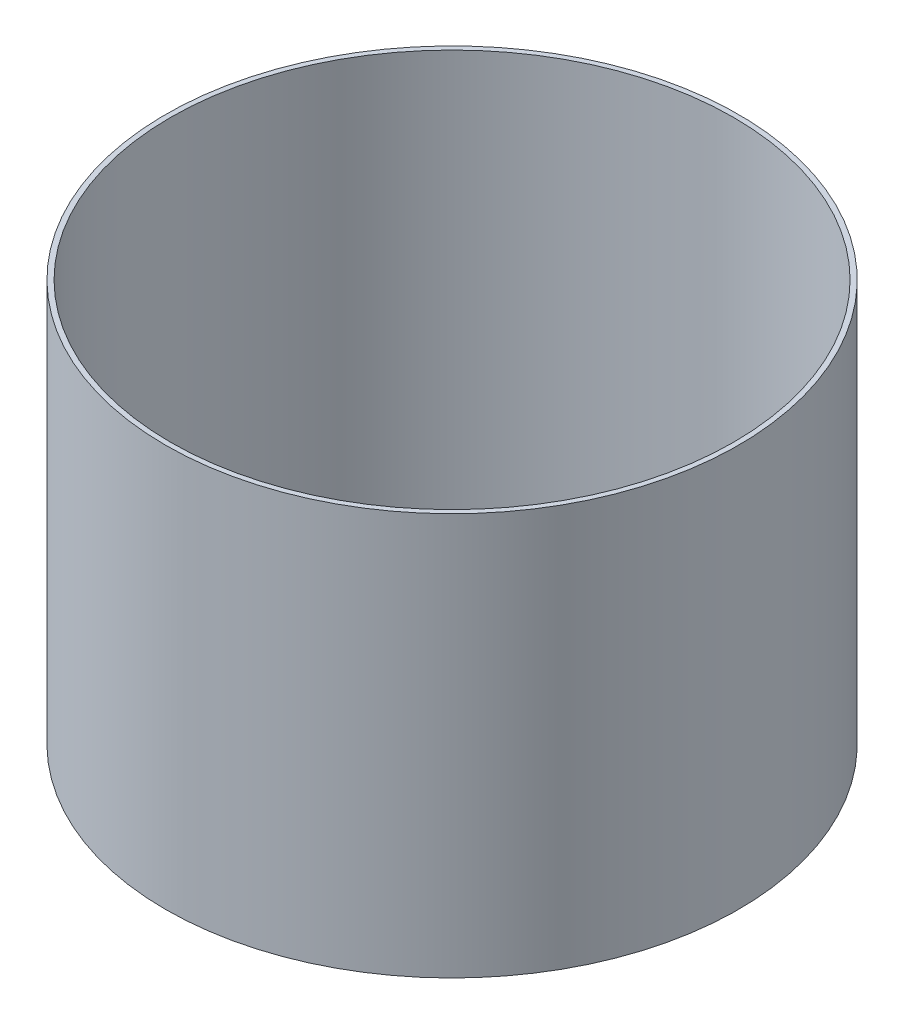
SolidWorks part; units mm, degrees
ref_plane "Front Plane" through (0, 0, 0) normal (0, 0, 1) x (1, 0, 0)
ref_plane "Top Plane" through (0, 0, 0) normal (0, 1, 0) x (1, 0, 0)
ref_plane "Right Plane" through (0, 0, 0) normal (1, 0, 0) x (0, 0, -1)
sketch "Sketch1" plane through (0, 0, 0) normal (0, 1, 0) x (1, 0, 0)
  circle A0 centre (0, 0) radius 28.5
  circle A1 centre (0, 0) radius 28
  dimension "D1" = 57
  dimension "D2" = 56
extrude "Boss-Extrude1" add sketch "Sketch1" along normal blind 40
